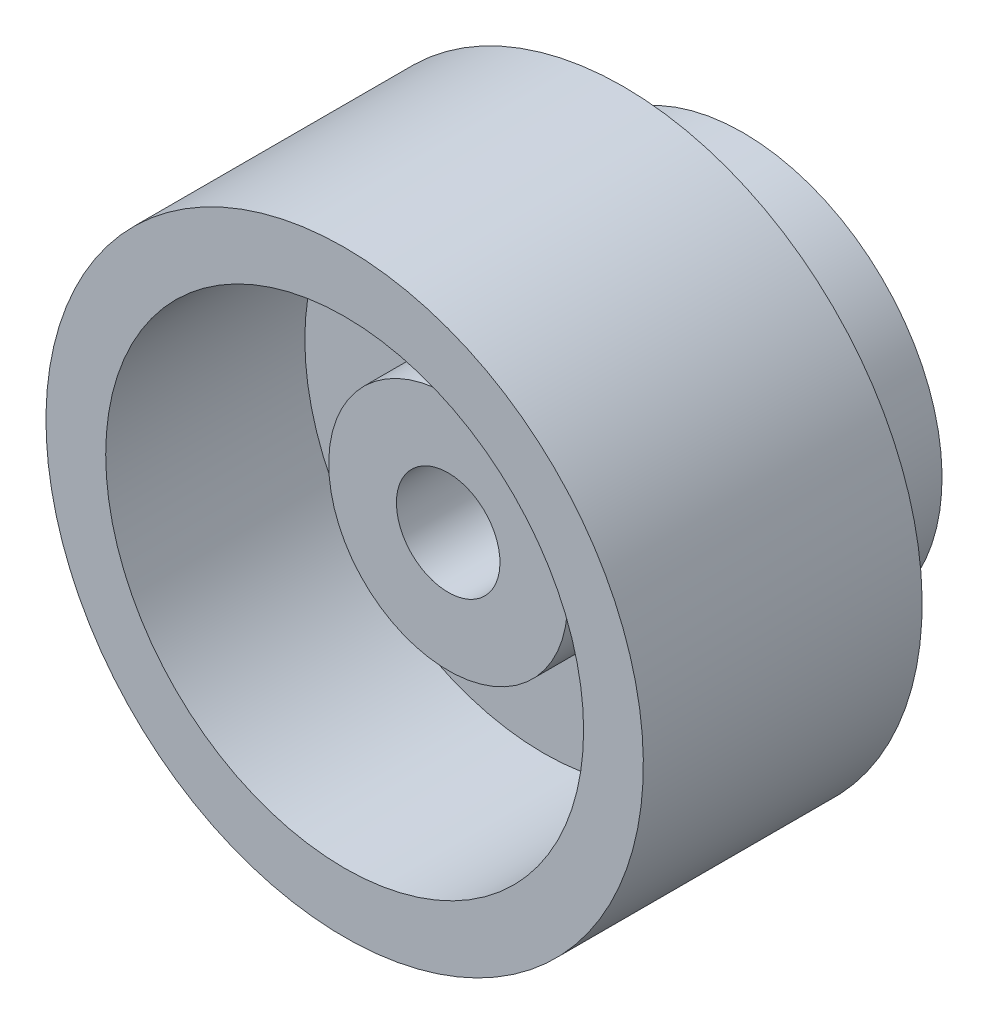
SolidWorks part; units mm, degrees
ref_plane "Front Plane" through (0, 0, 0) normal (0, 0, 1) x (1, 0, 0)
ref_plane "Top Plane" through (0, 0, 0) normal (0, 1, 0) x (1, 0, 0)
ref_plane "Right Plane" through (0, 0, 0) normal (1, 0, 0) x (0, 0, -1)
sketch "Sketch2" plane through (0, 0, 0) normal (1, 0, 0) x (0, 0, -1)
  line L1 (-12, 6.5) -> (-12, 15)
  line L2 (-12, 15) -> (0, 15)
  line L3 (0, 15) -> (0, 30)
  line L4 (0, 30) -> (-25, 30)
  line L5 (-25, 30) -> (-25, 37.5)
  line L6 (-25, 37.5) -> (10, 37.5)
  line L7 (10, 37.5) -> (10, 25)
  line L8 (10, 25) -> (25, 25)
  line L9 (25, 25) -> (25, 6.5)
  line L11 (-12, 6.5) -> (25, 6.5)
  line L12 (25, 0) -> (-25, 0) construction
  point P9 (0, 0)
  dimension "D1" = 25
  dimension "D2" = 37
  dimension "D3" = 50
  dimension "D4" = 15
  dimension "D5" = 8.5
  dimension "D6" = 37.5
  dimension "D7" = 15
  dimension "D8" = 25
  dimension "D9" = 30
  dimension "D10" = 50
revolve "Revolve1" add sketch "Sketch2" angle 360 about L12
